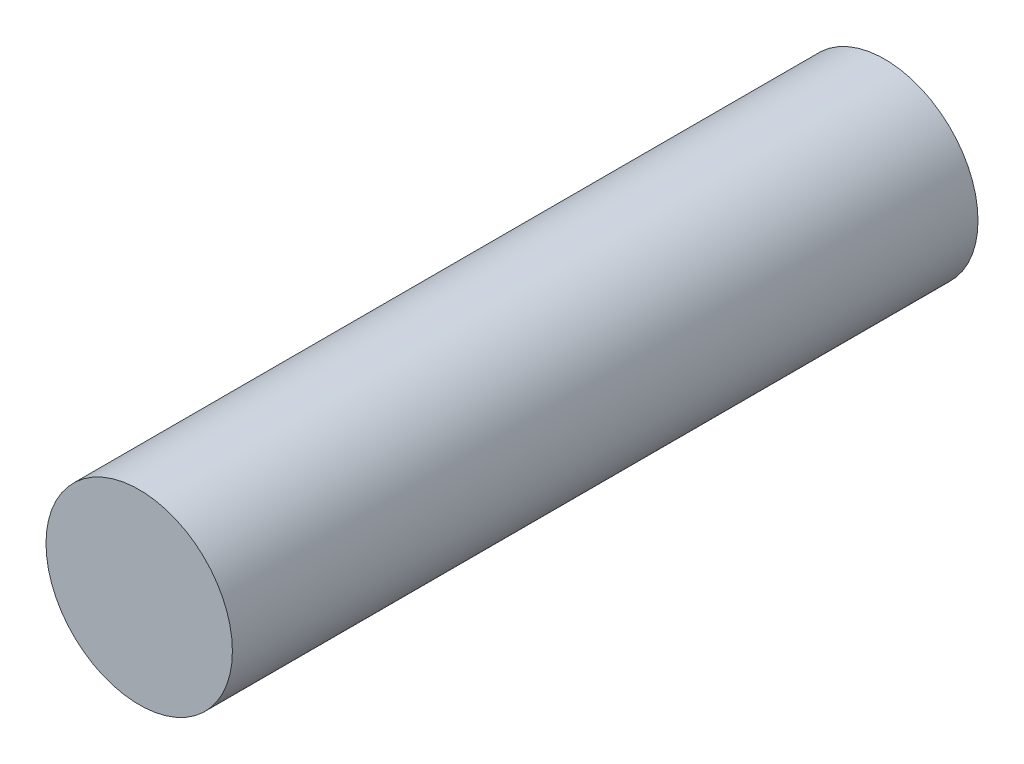
SolidWorks part; units mm, degrees
material "黄铜"
ref_plane "前视基准面" through (0, 0, 0) normal (0, 0, 1) x (1, 0, 0)
ref_plane "上视基准面" through (0, 0, 0) normal (0, 1, 0) x (1, 0, 0)
ref_plane "右视基准面" through (0, 0, 0) normal (1, 0, 0) x (0, 0, -1)
sketch "草图1" plane through (0, 0, 0) normal (0, 0, 1) x (1, 0, 0)
  circle A0 centre (-9.462, 6.0213) radius 1.375
  dimension "D1" = 2.75
extrude "凸台-拉伸1" add sketch "草图1" along normal blind 11
